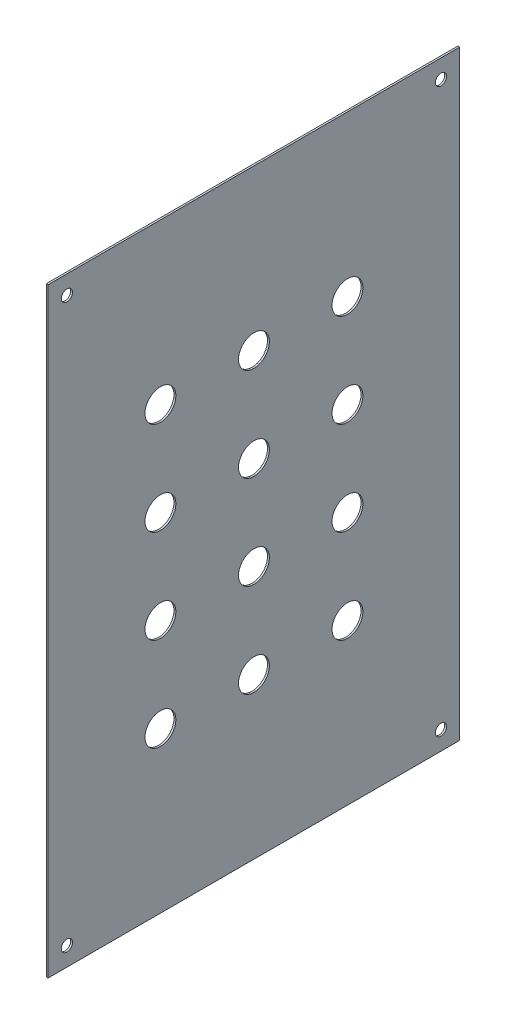
SolidWorks part; units mm, degrees
ref_plane "Front Plane" through (0, 0, 0) normal (1, 0, 0) x (0, 1, 0)
ref_plane "Top Plane" through (0, 0, 0) normal (0, 0, 1) x (0, 1, 0)
ref_plane "Right Plane" through (0, 0, 0) normal (0, 1, 0) x (-1, 0, 0)
sketch "Sketch1" plane through (0, 0, 0) normal (1, 0, 0) x (0, 1, 0)
  line L1 (-160.5, -110) -> (160.5, -110)
  line L2 (-160.5, -110) -> (-160.5, 110)
  line L3 (-160.5, 110) -> (160.5, 110)
  line L4 (160.5, -110) -> (160.5, 110)
  line L5 (-160.5, -110) -> (160.5, 110) construction
  line L6 (-160.5, 110) -> (160.5, -110) construction
  point P0 (0, 0)
  dimension "D1" = 321
  dimension "D2" = 220
extrude "Boss-Extrude1" add sketch "Sketch1" along normal blind 1
sketch "Sketch2" plane through (1, 0, 0) normal (1, 0, 0) x (0, 1, 0)
  line L0 (0, 0) -> (-75, 0) construction
  line L1 (-75, 0) -> (-75, 50) construction
  circle A0 centre (-75, 50) radius 8.25
  circle A1 centre (-25, 50) radius 8.25
  circle A2 centre (25, 50) radius 8.25
  circle A3 centre (75, 50) radius 8.25
  circle A4 centre (-25, 0) radius 8.25
  circle A5 centre (25, 0) radius 8.25
  circle A6 centre (75, 0) radius 8.25
  circle A7 centre (-25, -50) radius 8.25
  circle A8 centre (25, -50) radius 8.25
  circle A9 centre (75, -50) radius 8.25
  circle A10 centre (-75, 0) radius 8.25
  circle A11 centre (-75, -50) radius 8.25
  dimension "D1" = 16.5
  dimension "D6" = 50
  dimension "D4" = 75
  dimension "D5" = 50
  dimension "D2" = 4
  dimension "D3" = 3
extrude "Cut-Extrude1" cut sketch "Sketch2" against normal through all
sketch "Sketch3" plane through (1, 0, 0) normal (1, 0, 0) x (0, 1, 0)
  line L0 (0, 110) -> (0, -110) construction
  line L1 (160.5, 110) -> (-160.5, 110) construction
  line L2 (-160.5, -110) -> (160.5, -110) construction
  line L4 (-160.5, 110) -> (-160.5, -110) construction
  line L5 (-160.5, 0) -> (160.5, 0) construction
  line L6 (160.5, -110) -> (160.5, 110) construction
  circle A0 centre (-150.5, 100) radius 3
  circle A1 centre (150.5, 100) radius 3
  circle A2 centre (-150.5, -100) radius 3
  circle A3 centre (150.5, -100) radius 3
  dimension "D3" = 6
  dimension "D1" = 10
  dimension "D2" = 10
extrude "Cut-Extrude2" cut sketch "Sketch3" against normal through all
